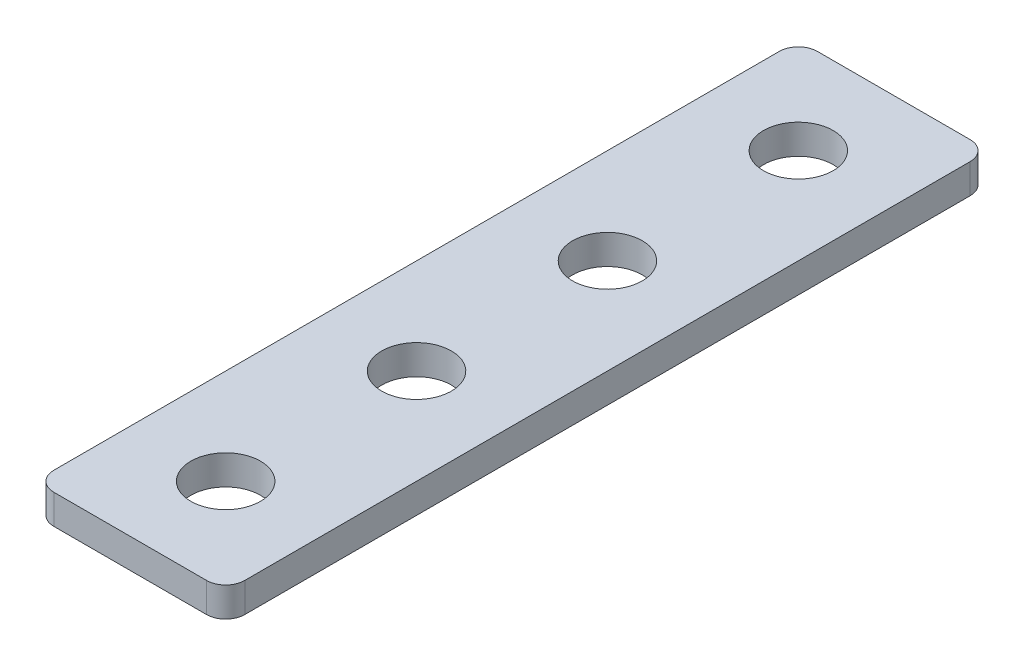
SolidWorks part; units mm, degrees
ref_plane "Front Plane" through (0, 0, 0) normal (0, 0, 1) x (1, 0, 0)
ref_plane "Top Plane" through (0, 0, 0) normal (0, 1, 0) x (1, 0, 0)
ref_plane "Right Plane" through (0, 0, 0) normal (1, 0, 0) x (0, 0, -1)
sketch "Sketch1" plane through (0, 0, 0) normal (0, 1, 0) x (1, 0, 0)
  line L0 (0, 39.2) -> (0, -39.2) construction
  line L1 (-5, 20) -> (5, 20)
  line L2 (-5, 20) -> (-5, -20)
  line L3 (-5, -20) -> (5, -20)
  line L4 (5, 20) -> (5, -20)
  line L5 (-5, 20) -> (5, -20) construction
  line L6 (-5, -20) -> (5, 20) construction
  circle A0 centre (0, 15) radius 1.825
  circle A1 centre (0, 5) radius 1.825
  circle A2 centre (0, -5) radius 1.825
  circle A3 centre (0, -15) radius 1.825
  point P0 (0, 0)
  point P9 (0, 0)
  dimension "D4" = 3.65
  dimension "D1" = 10
  dimension "D2" = 40
  dimension "D3" = 5
  dimension "D5" = 4
extrude "Boss-Extrude1" add sketch "Sketch1" along normal blind 1.55
fillet "Fillet1" radius 1 4 edges at (5, 0.775, 20) (-5, 0.775, 20) (5, 0.775, -20) (-5, 0.775, -20)
